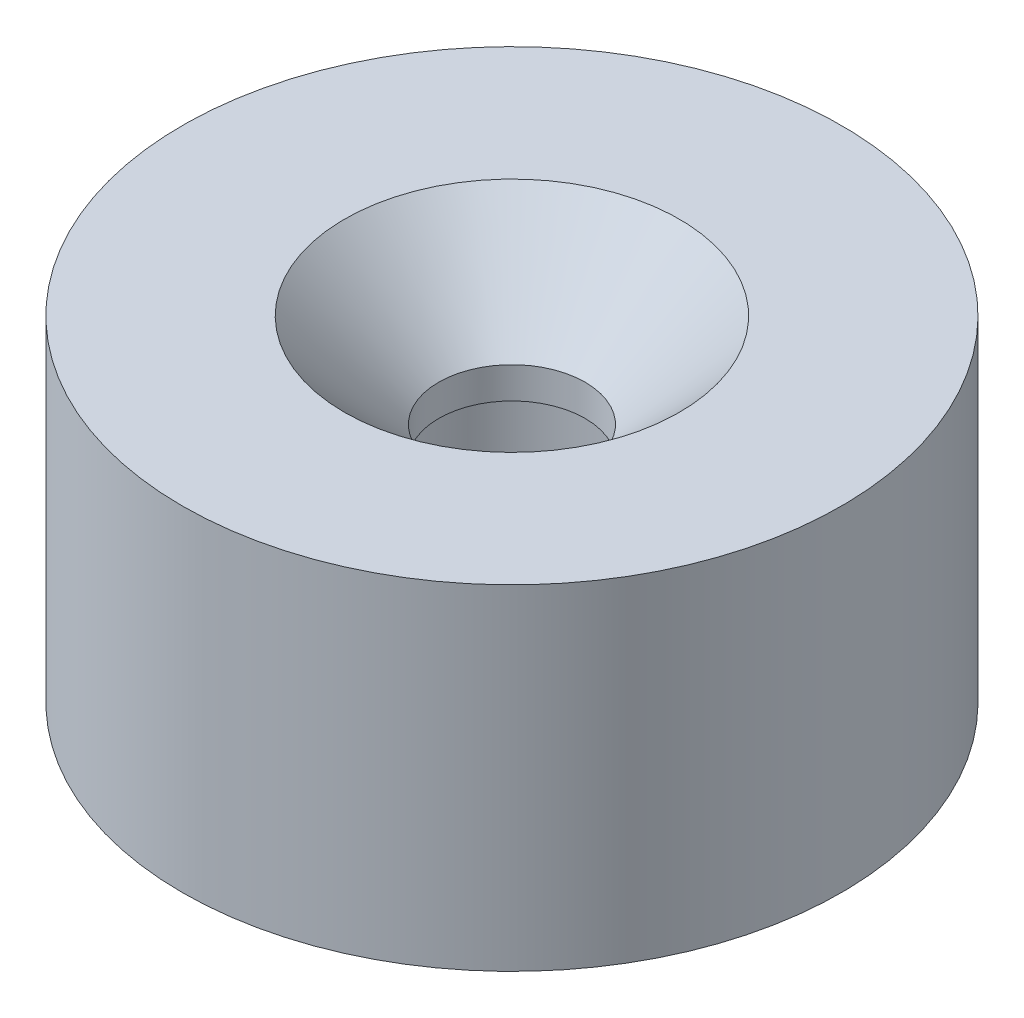
SolidWorks part; units mm, degrees
ref_plane "Front Plane" through (0, 0, 0) normal (0, 0, 1) x (1, 0, 0)
ref_plane "Top Plane" through (0, 0, 0) normal (0, 1, 0) x (1, 0, 0)
ref_plane "Right Plane" through (0, 0, 0) normal (1, 0, 0) x (0, 0, -1)
sketch "Sketch1" plane through (0, 0, 0) normal (0, 1, 0) x (1, 0, 0)
  circle A0 centre (0, 0) radius 7.875
  circle A1 centre (0, 0) radius 1.75
  dimension "D1" = 15.75
  dimension "D2" = 3.5
extrude "Boss-Extrude1" add sketch "Sketch1" along normal blind 8
sketch "Sketch2" plane through (0, 8, 0) normal (0, 1, 0) x (1, 0, 0)
  circle A0 centre (0, 0) radius 4
  circle A1 centre (0, 0) radius 1.75 construction
  dimension "D1" = 8
extrude "Cut-Extrude1" cut sketch "Sketch2" against normal blind 3 draft 45
sketch "Sketch3" plane through (0, 0, 0) normal (0, -1, 0) x (-1, 0, 0)
  circle A0 centre (0, 0) radius 4
  circle A1 centre (0, 0) radius 1.75 construction
  dimension "D1" = 8
extrude "Cut-Extrude2" cut sketch "Sketch3" against normal blind 5
sketch "Sketch4" plane through (0, 5, 0) normal (0, -1, 0) x (1, 0, 0)
  circle A0 centre (0, 0) radius 2.5
  circle A1 centre (0, 0) radius 4
  circle A2 centre (0, 0) radius 4 construction
  dimension "D1" = 5
extrude "Boss-Extrude2" add sketch "Sketch4" along normal blind 2
